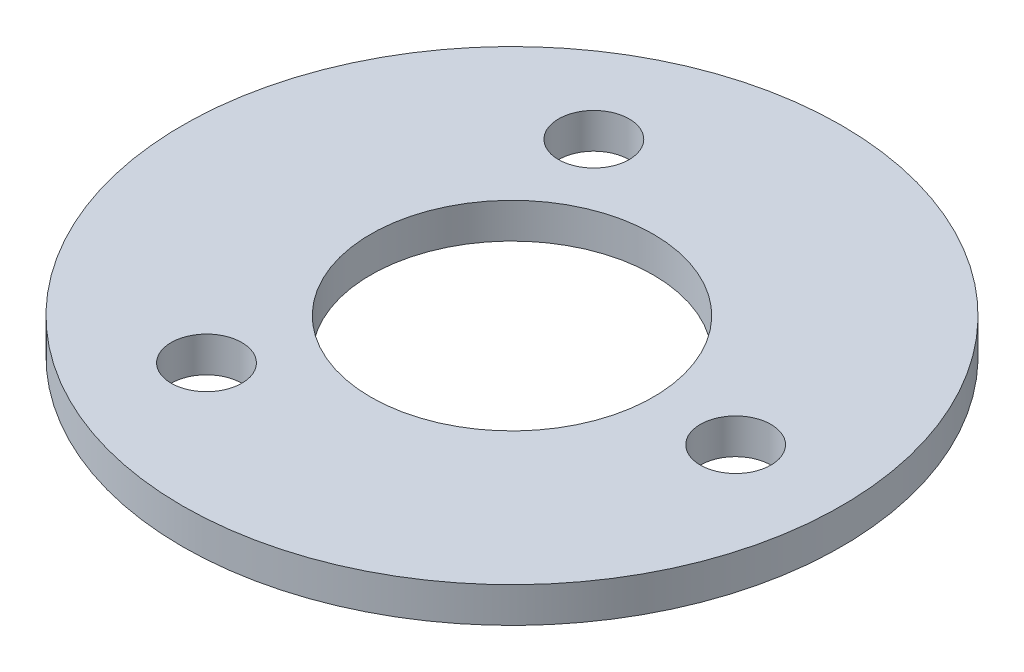
SolidWorks part; units mm, degrees
ref_plane "前视基准面" through (0, 0, 0) normal (0, 0, 1) x (1, 0, 0)
ref_plane "上视基准面" through (0, 0, 0) normal (0, 1, 0) x (1, 0, 0)
ref_plane "右视基准面" through (0, 0, 0) normal (1, 0, 0) x (0, 0, -1)
other "Configuration Table"
sketch "草图1" plane through (0, 0, 0) normal (0, 1, 0) x (1, 0, 0)
  circle A0 centre (0, 0) radius 6
  circle A1 centre (0, 0) radius 14
  dimension "D1" = 12
  dimension "D2" = 28
extrude "凸台-拉伸1" add sketch "草图1" along normal blind 1.5
sketch "草图2" plane through (0, 0, 0) normal (0, 1, 0) x (1, 0, 0)
  line L0 (-29.4912, 0) -> (27.9308, 0) construction
  line L1 (0, 23.0156) -> (0, -24.8881) construction
  line L2 (9.5, 23.0156) -> (9.5, -24.8881) construction
  circle A0 centre (9.5, 0) radius 1.5
  circle A1 centre (-4.75, -8.2272) radius 1.5
  circle A2 centre (-4.75, 8.2272) radius 1.5
  point P15 (0, 0)
  dimension "D2" = 3
  dimension "D1" = 9.5
  dimension "D3" = 3
extrude "切除-拉伸2" cut sketch "草图2" along normal up to next
